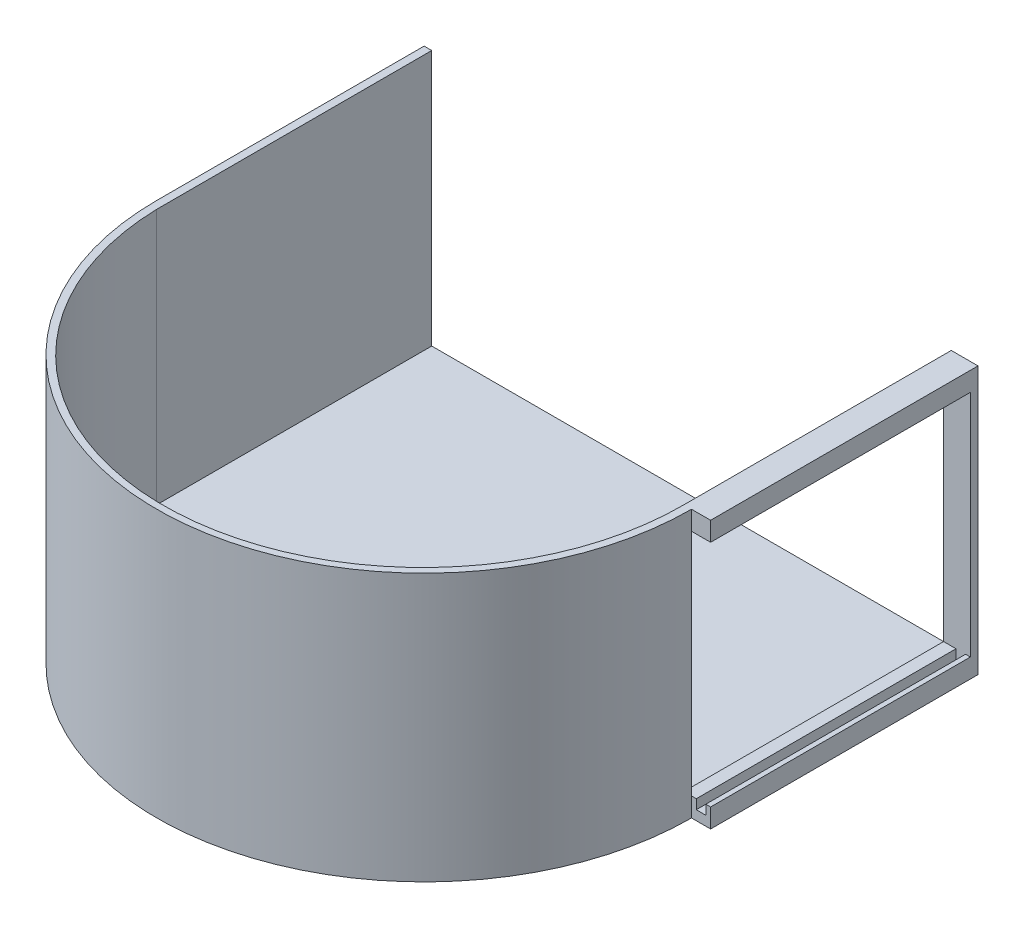
SolidWorks part; units mm, degrees
ref_plane "Front Plane" through (0, 0, 0) normal (0, 0, 1) x (1, 0, 0)
ref_plane "Top Plane" through (0, 0, 0) normal (0, 1, 0) x (1, 0, 0)
ref_plane "Right Plane" through (0, 0, 0) normal (1, 0, 0) x (0, 0, -1)
sketch "Sketch1" plane through (0, 0, 0) normal (0, 1, 0) x (1, 0, 0)
  line L2 (0, 0) -> (0, 88.9)
  line L3 (0, 88.9) -> (177.8, 88.9)
  line L4 (177.8, 0) -> (177.8, 88.9)
  arc A0 (0, 0) -> (177.8, 0) centre (88.9, 0) ccw
  dimension "D1" = 177.8
  dimension "D2" = 88.9
extrude "Boss-Extrude1" add sketch "Sketch1" along normal blind 88.9
sketch "Sketch2" plane through (0, 88.9, 0) normal (0, 1, 0) x (1, 0, 0)
  line L0 (177.8, 88.9) -> (0, 88.9) construction
  line L1 (2.54, 88.9) -> (175.26, 88.9)
  line L2 (2.54, 88.9) -> (2.54, -2.54)
  line L4 (175.26, 88.9) -> (175.26, 0)
  line L5 (177.8, 0) -> (177.8, 88.9) construction
  arc A0 (2.54, -2.54) -> (175.26, 0) centre (88.8861, -0.3272) ccw
  arc A1 (0, 0) -> (177.8, 0) centre (88.9, 0) ccw construction
  point P6 (90.1562, -86.6924)
  point P14 (88.9, -88.9)
  dimension "D1" = 0
  dimension "D2" = 2.54
  dimension "D3" = 2.54
  dimension "D4" = 88.9
  dimension "D5" = 2.54
extrude "Cut-Extrude1" cut sketch "Sketch2" against normal blind 85.09
sketch "Sketch4" plane through (177.8, 0, 0) normal (1, 0, 0) x (0, 0, -1)
  line L0 (0, 88.9) -> (88.9, 88.9)
  line L1 (88.9, 88.9) -> (88.9, 0)
  line L2 (88.9, 0) -> (0, 0)
  line L3 (0, 0) -> (0, 6.35)
  line L4 (0, 88.9) -> (0, 0) construction
  line L5 (0, 6.35) -> (86.36, 6.35)
  line L6 (86.36, 6.35) -> (86.36, 82.55)
  line L7 (86.36, 82.55) -> (0, 82.55)
  line L8 (0, 82.55) -> (0, 88.9)
  dimension "D1" = 6.35
  dimension "D2" = 6.35
  dimension "D3" = 2.54
extrude "Boss-Extrude3" add sketch "Sketch4" along normal blind 6.35
sketch "Sketch6" plane through (0, 6.35, 0) normal (0, 1, 0) x (1, 0, 0)
  line L0 (184.15, 0) -> (177.8, 0) construction
  line L1 (179.3875, 0) -> (182.5625, 0)
  line L2 (179.3875, 0) -> (179.3875, 86.36)
  line L3 (179.3875, 86.36) -> (182.5625, 86.36)
  line L4 (182.5625, 0) -> (182.5625, 86.36)
  dimension "D1" = 3.175
  dimension "D2" = 1.5875
  dimension "D3" = 86.36
extrude "Cut-Extrude2" cut sketch "Sketch6" against normal blind 3.175
sketch "Sketch7" plane through (177.8, 0, 0) normal (1, 0, 0) x (0, 0, -1)
  line L1 (0, 82.55) -> (86.36, 82.55)
  line L2 (0, 82.55) -> (0, 6.35)
  line L3 (0, 6.35) -> (86.36, 6.35)
  line L4 (86.36, 82.55) -> (86.36, 6.35)
extrude "Cut-Extrude3" cut sketch "Sketch7" against normal blind 2.54
equation "\"0.`\"=0.25"
